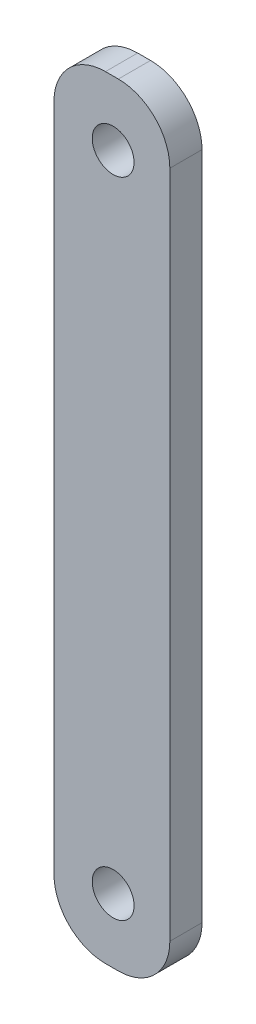
SolidWorks part; units mm, degrees
ref_plane "정면" through (0, 0, 0) normal (0, 0, 1) x (1, 0, 0)
ref_plane "윗면" through (0, 0, 0) normal (0, 1, 0) x (1, 0, 0)
ref_plane "우측면" through (0, 0, 0) normal (1, 0, 0) x (0, 0, -1)
sketch "스케치1" plane through (0, 0, 0) normal (0, 0, 1) x (1, 0, 0)
  line L0 (-19.4952, 100.9558) -> (40.2816, 100.9558)
  line L1 (-9.1933, 110.9558) -> (8.8067, 110.9558)
  line L2 (-9.1933, 110.9558) -> (-9.1933, -9.0442)
  line L3 (-9.1933, -9.0442) -> (8.8067, -9.0442)
  line L4 (8.8067, 110.9558) -> (8.8067, -9.0442)
  line L5 (-17.1798, 0.9558) -> (36.8284, 0.9558)
  dimension "D1" = 18
  dimension "D2" = 120
  dimension "D3" = 10
  dimension "D4" = 100
extrude "보스-돌출1" add sketch "스케치1" along normal blind 5 contours L2 L3 L4 L1
sketch "스케치2" plane through (0, 0, 5) normal (0, 0, 1) x (1, 0, 0)
  line L0 (-26.2248, 100.9558) -> (41.5265, 100.9558)
  line L1 (-9.1933, 110.9558) -> (8.8067, 110.9558) construction
  line L2 (-30.4592, 0.9558) -> (55.3277, 0.9558)
  line L3 (-9.1933, -9.0442) -> (8.8067, -9.0442) construction
  circle A0 centre (0, 100.9558) radius 3.25
  circle A1 centre (0, 0.9558) radius 3.25
  dimension "D3" = 6.5
  dimension "D4" = 6.5
  dimension "D1" = 10
  dimension "D2" = 10
extrude "컷-돌출1" cut sketch "스케치2" against normal blind 30 contours A1 | A0
fillet "필렛1" radius 8 4 edges at (-9.1933, -9.0442, 2.5) (8.8067, -9.0442, 2.5) (-9.1933, 110.9558, 2.5) (8.8067, 110.9558, 2.5)
